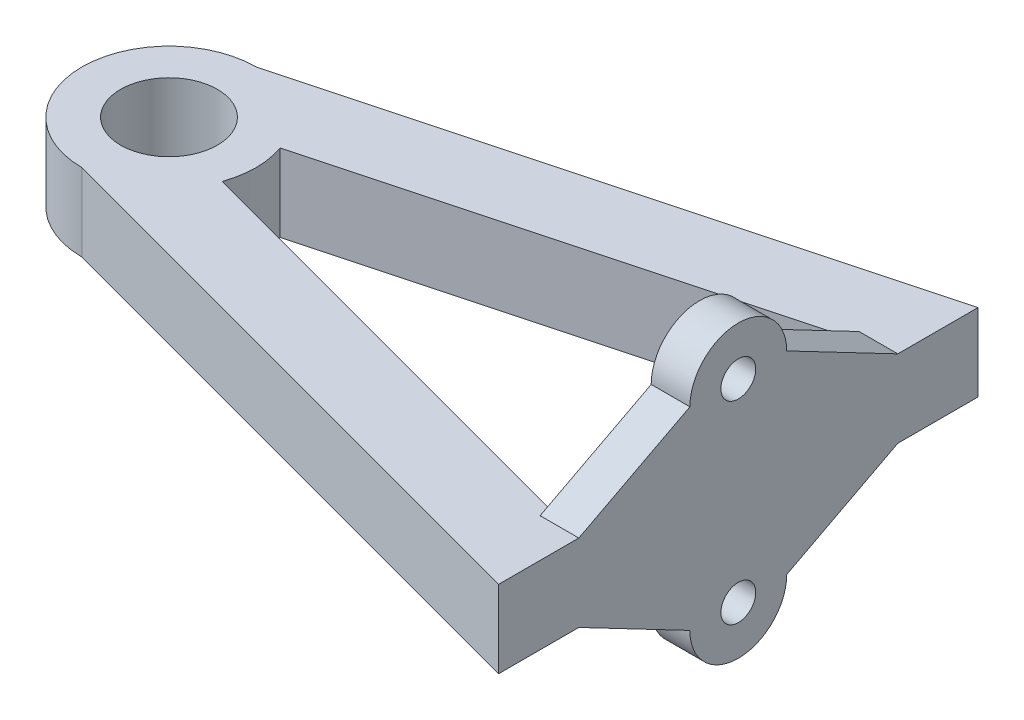
SolidWorks part; units mm, degrees
ref_plane "Front Plane" through (0, 0, 0) normal (0, 0, 1) x (1, 0, 0)
ref_plane "Top Plane" through (0, 0, 0) normal (0, 1, 0) x (1, 0, 0)
ref_plane "Right Plane" through (0, 0, 0) normal (1, 0, 0) x (0, 0, -1)
sketch "Sketch1" plane through (0, 0, 0) normal (0, 1, 0) x (1, 0, 0)
  line L0 (0, 0) -> (73.5, 0) construction
  line L1 (0, 11.25) -> (73.5, 30.9443)
  line L2 (73.5, 30.9443) -> (73.5, 20.5915)
  line L3 (73.5, 20.5915) -> (10.6101, 3.7402)
  line L4 (73.5, -20.5915) -> (10.6101, -3.7402)
  line L5 (73.5, -30.9443) -> (73.5, -20.5915)
  line L6 (0, -11.25) -> (73.5, -30.9443)
  circle A0 centre (0, 0) radius 6.25
  arc A1 (0, 11.25) -> (0, -11.25) centre (0, 0) ccw
  arc A2 (10.6101, -3.7402) -> (10.6101, 3.7402) centre (0, 0) ccw
  dimension "D2" = 12.5
  dimension "D5" = 5
  dimension "D1" = 73.5
  dimension "D3" = 15
  dimension "D4" = 10
extrude "Boss-Extrude1" add sketch "Sketch1" along normal blind 10
sketch "Sketch2" plane through (73.5, 0, 0) normal (1, 0, 0) x (0, 0, -1)
  line L0 (-20.5915, 5) -> (-7.678, 5) construction
  line L1 (-20.5915, 10) -> (-20.5915, 0) construction
  line L2 (0, 0) -> (0, 4.3114) construction
  line L3 (-20.5915, 10) -> (-6.25, 17.5)
  line L4 (6.25, 17.5) -> (20.5915, 10)
  line L5 (6.25, -7.5) -> (20.5915, 0)
  line L6 (-20.5915, 0) -> (-6.25, -7.5)
  line L7 (20.5915, 10) -> (20.5915, 0) construction
  line L8 (20.5915, 10) -> (20.5915, 0)
  line L9 (-20.5915, 10) -> (-20.5915, 0)
  circle A0 centre (0, 17.5) radius 2.25
  circle A1 centre (0, -7.5) radius 2.25
  arc A2 (6.25, 17.5) -> (-6.25, 17.5) centre (0, 17.5) ccw
  arc A3 (-6.25, -7.5) -> (6.25, -7.5) centre (0, -7.5) ccw
  dimension "D3" = 4.5
  dimension "D4" = 4
  dimension "D1" = 25
extrude "Boss-Extrude2" add sketch "Sketch2" against normal blind 5
